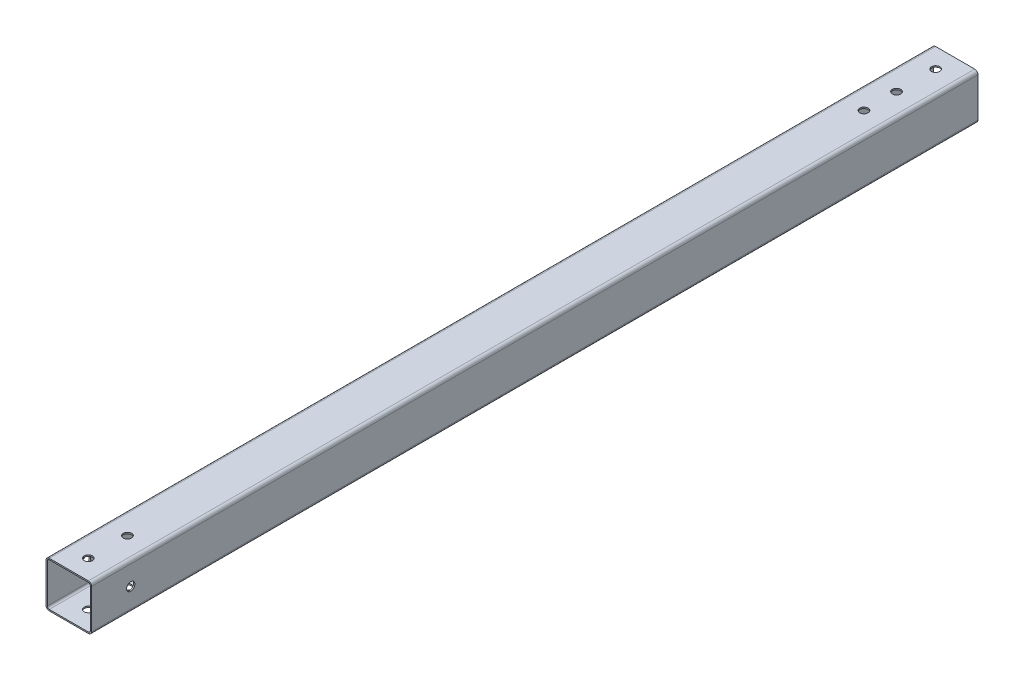
SolidWorks part; units mm, degrees
ref_plane "Alzado" through (0, 0, 0) normal (0, 0, 1) x (1, 0, 0)
ref_plane "Planta" through (0, 0, 0) normal (0, 1, 0) x (1, 0, 0)
ref_plane "Vista lateral" through (0, 0, 0) normal (1, 0, 0) x (0, 0, -1)
sketch "Croquis1" plane through (0, 0, 0) normal (1, 0, 0) x (0, 0, -1)
  line L0 (680, 0) -> (-680, 0)
  point P4 (0, 0)
  dimension "D1" = 1360
other "Tubo cuadrado 3 X 3 X 0.25(1)"
ref_plane "Plano1" through (0, 0, -680) normal (0, 0, 1) x (0, -1, 0)
sketch "Sketch1" plane through (0, 0, -680) normal (0, 0, 1) x (0, -1, 0)
  line L0 (-30, -33) -> (30, -33)
  line L1 (-33, -30) -> (-33, 30)
  line L2 (30, 33) -> (-30, 33)
  line L3 (33, 30) -> (33, -30)
  line L4 (-30, -35) -> (30, -35)
  line L5 (-35, -30) -> (-35, 30)
  line L6 (30, 35) -> (-30, 35)
  line L7 (35, 30) -> (35, -30)
  line L8 (0, 0) -> (33, 0) construction
  line L9 (0, 0) -> (0, 33) construction
  arc A0 (35, 30) -> (30, 35) centre (30, 30) ccw
  arc A1 (30, -35) -> (35, -30) centre (30, -30) ccw
  arc A2 (-35, -30) -> (-30, -35) centre (-30, -30) ccw
  arc A3 (-30, 35) -> (-35, 30) centre (-30, 30) ccw
  arc A4 (-30, 33) -> (-33, 30) centre (-30, 30) ccw
  arc A5 (33, 30) -> (30, 33) centre (30, 30) ccw
  arc A6 (30, -33) -> (33, -30) centre (30, -30) ccw
  arc A7 (-33, -30) -> (-30, -33) centre (-30, -30) ccw
  point P3 (0, 35)
  point P4 (35, 0)
  point P5 (0, -35)
  point P6 (-35, 0)
  point P7 (-35, 35)
  point P8 (-35, -35)
  point P33 (0, 0)
  point P35 (35, -35)
  point P36 (35, 35)
  point P37 (0, 0)
  dimension "D1" = 5
  dimension "Thickness" = 2
  dimension "V_leg" = 70
sketch "Croquis3" plane through (0, -35, 0) normal (0, -1, 0) x (1, 0, 0)
  line L0 (0, -680) -> (0, 680) construction
  line L1 (-30, 680) -> (30, 680) construction
  line L2 (0, 0) -> (240.4919, 0) construction
  line L3 (-30, -680) -> (30, -680) construction
  circle A0 centre (0, 650) radius 6.35
  circle A1 centre (0, 590) radius 6.35
  circle A2 centre (0, -590) radius 6.35
  circle A3 centre (0, -650) radius 6.35
  circle A4 centre (0, -540) radius 6.35
  dimension "D2" = 12.7
  dimension "D4" = 12.7
  dimension "D5" = 12.7
  dimension "D1" = 30
  dimension "D3" = 60
  dimension "D6" = 140
extrude "Cortar-Extruir1" cut sketch "Croquis3" against normal through all
sketch "Croquis4" plane through (-35, 0, 0) normal (-1, 0, 0) x (0, 0, 1)
  line L0 (680, 0) -> (512.3684, 0) construction
  line L1 (-680, 0) -> (680, 0) construction
  line L2 (680, 30) -> (680, -30) construction
  circle A0 centre (620, 0) radius 6.35
  dimension "D1" = 12.7
  dimension "D2" = 60
extrude "Cortar-Extruir2" cut sketch "Croquis4" against normal through all
